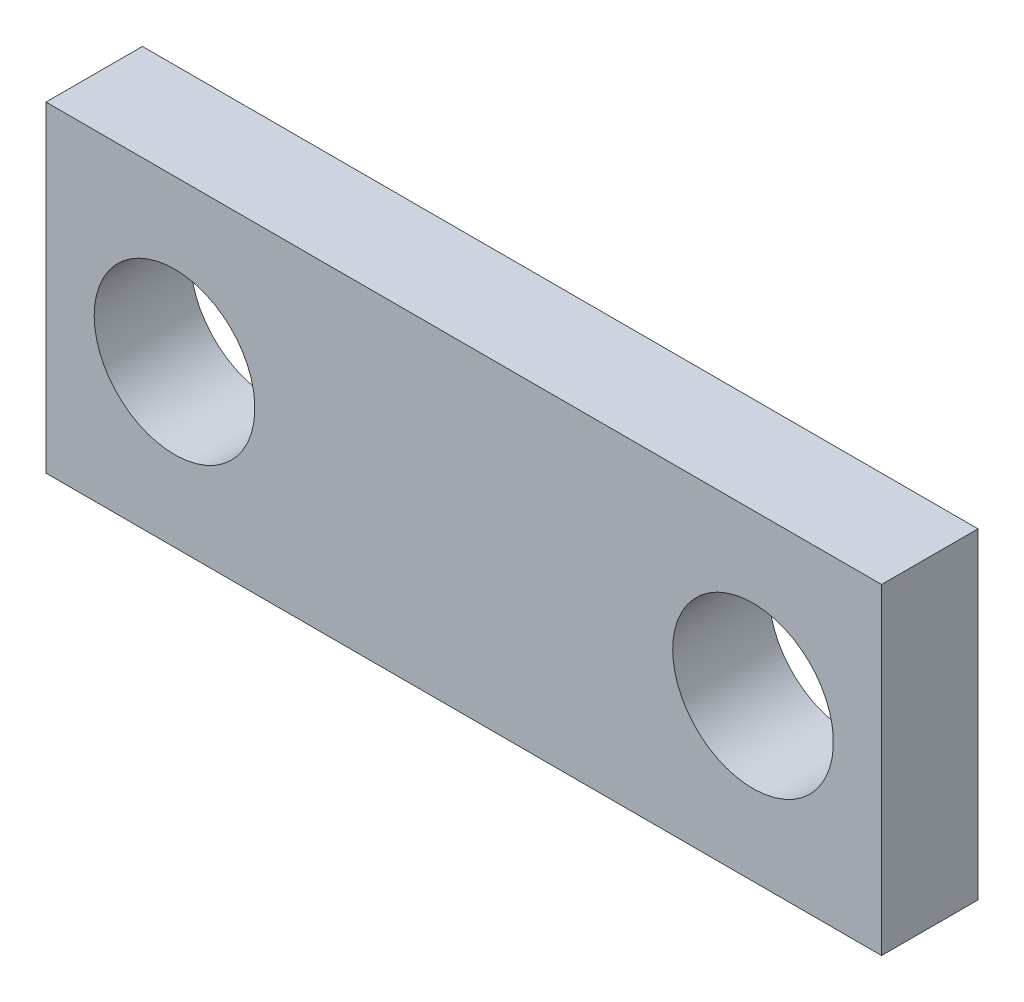
SolidWorks part; units mm, degrees
material "1023 Листовая углеродистая сталь (SS)"
ref_plane "Спереди" through (0, 0, 0) normal (0, 0, 1) x (1, 0, 0)
ref_plane "Сверху" through (0, 0, 0) normal (0, 1, 0) x (1, 0, 0)
ref_plane "Справа" through (0, 0, 0) normal (1, 0, 0) x (0, 0, -1)
ref_plane "Плоскость4" through (0, 0, 3) normal (0, 0, 1) x (1, 0, 0)
sketch "Эскиз1" plane through (0, 0, 3) normal (0, 0, 1) x (1, 0, 0)
  line L0 (-13, -5) -> (13, -5)
  line L1 (13, -5) -> (13, 5)
  line L2 (13, 5) -> (-13, 5)
  line L3 (-13, 5) -> (-13, -5)
  circle A0 centre (9, 0) radius 2.5
  circle A1 centre (-9, 0) radius 2.5
extrude "Бобышка-Вытянуть1" add sketch "Эскиз1" against normal blind 3
